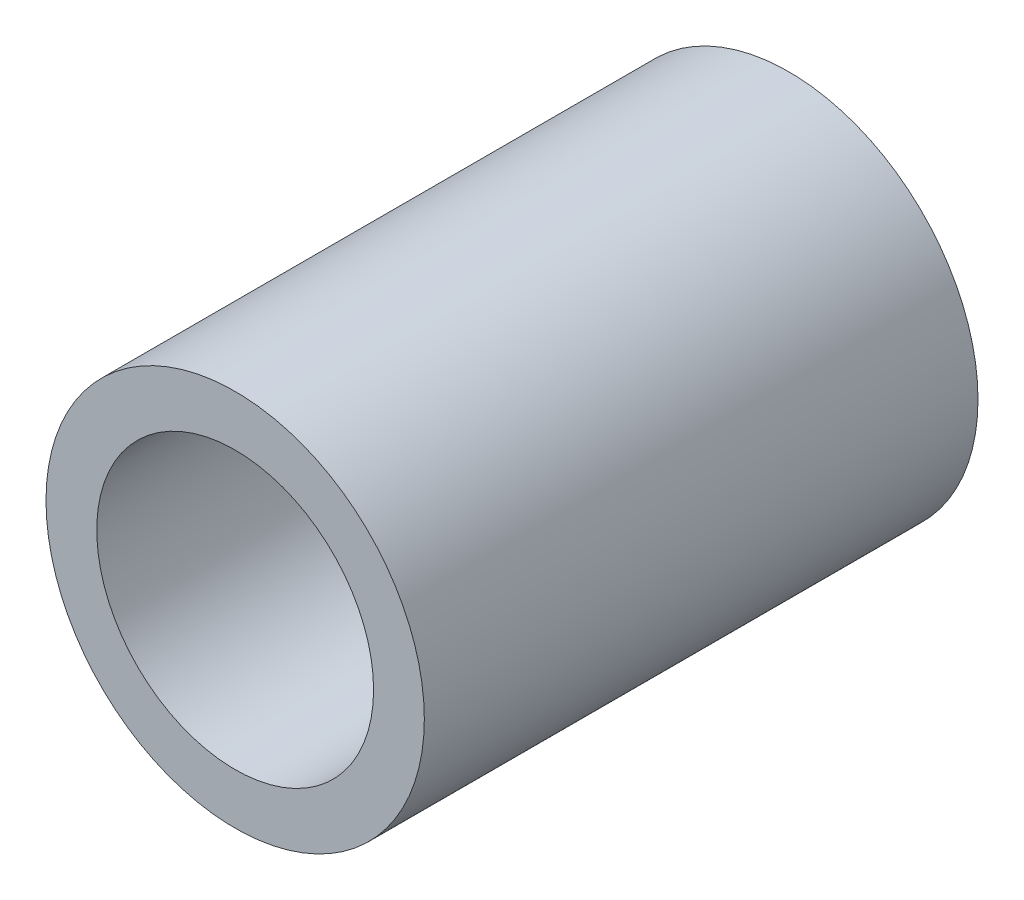
SolidWorks part; units mm, degrees
ref_plane "Front Plane" through (0, 0, 0) normal (0, 0, 1) x (1, 0, 0)
ref_plane "Top Plane" through (0, 0, 0) normal (0, 1, 0) x (1, 0, 0)
ref_plane "Right Plane" through (0, 0, 0) normal (1, 0, 0) x (0, 0, -1)
sketch "Sketch1" plane through (0, 0, 0) normal (0, 0, 1) x (1, 0, 0)
  circle A0 centre (0, 0) radius 41
  dimension "D1" = 82
extrude "Boss-Extrude1" add sketch "Sketch1" along normal blind 120
sketch "Sketch2" plane through (0, 0, 120) normal (0, 0, 1) x (1, 0, 0)
  circle A0 centre (0, 0) radius 30
  circle A1 centre (0, 0) radius 41 construction
  dimension "D1" = 11
extrude "Cut-Extrude1" cut sketch "Sketch2" against normal blind 130
